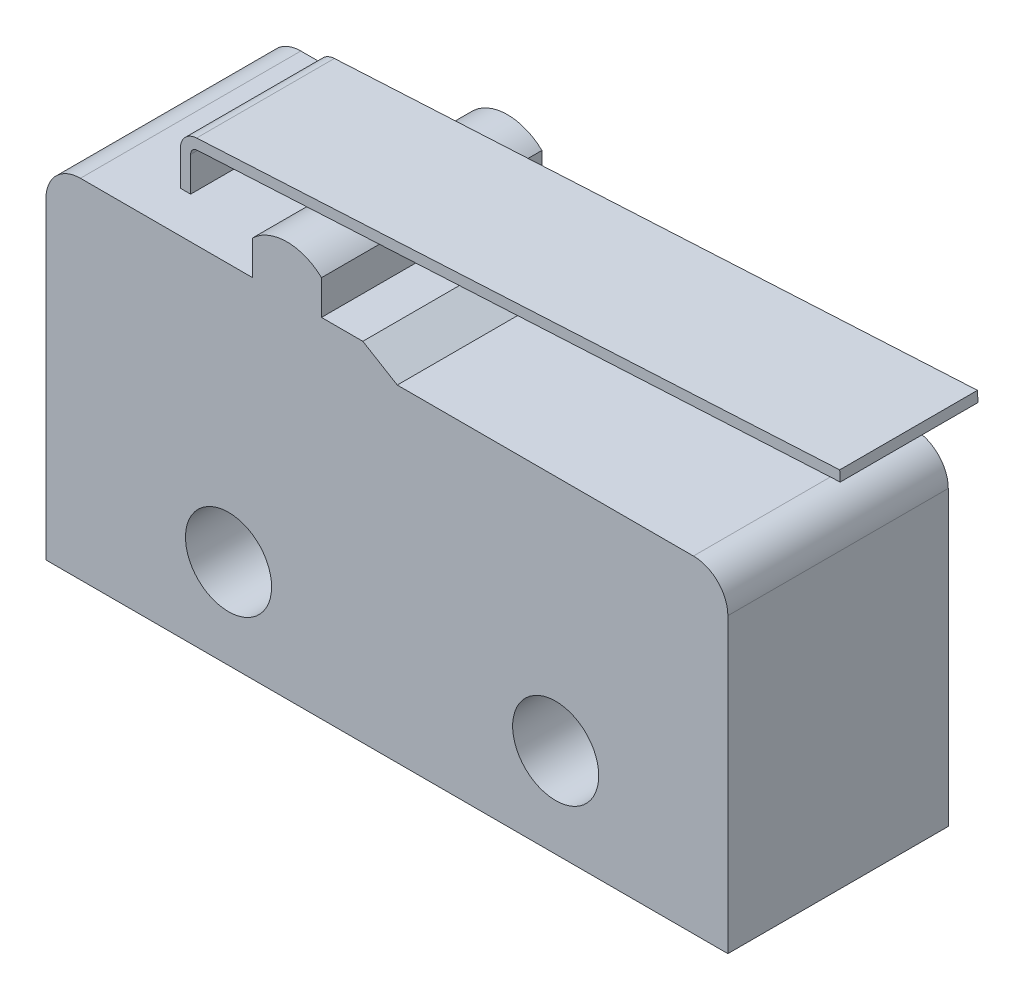
SolidWorks part; units mm, degrees
material "Nylon 6/10"
ref_plane "Front" through (0, 0, 0) normal (0, 0, 1) x (1, 0, 0)
ref_plane "Top" through (0, 0, 0) normal (0, 1, 0) x (1, 0, 0)
ref_plane "Right" through (0, 0, 0) normal (1, 0, 0) x (0, 0, -1)
sketch "Sketch1" plane through (0, 0, 0) normal (0, 0, 1) x (1, 0, 0)
  line L0 (-5.3, -2.6) -> (14.5, -2.6)
  line L1 (14.5, -2.6) -> (14.5, 5.9)
  line L2 (13.5, 6.9) -> (4.9, 6.9)
  line L3 (4.9, 6.9) -> (3.9, 7.5)
  line L4 (3.9, 7.5) -> (2.7, 7.5)
  line L5 (2.7, 7.5) -> (2.7, 8.5)
  line L6 (0.7, 8.5) -> (0.7, 7.5)
  line L7 (0.7, 7.5) -> (-4.3, 7.5)
  line L8 (-5.3, 6.5) -> (-5.3, -2.6)
  circle A0 centre (0, 0) radius 1.25
  circle A1 centre (9.5, 0) radius 1.25
  arc A2 (14.5, 5.9) -> (13.5, 6.9) centre (13.5, 5.9) ccw
  arc A3 (2.7, 8.5) -> (0.7, 8.5) centre (1.7, 7.45) ccw
  arc A4 (-4.3, 7.5) -> (-5.3, 6.5) centre (-4.3, 6.5) ccw
  dimension "D1" = 2.5
  dimension "D10" = 1
  dimension "D2" = 9.5
  dimension "D3" = 19.8
  dimension "D4" = 9.5
  dimension "D5" = 2.6
  dimension "D6" = 5.3
  dimension "D7" = 10.1
  dimension "D8" = 6
  dimension "D9" = 2
  dimension "D11" = 1.2
  dimension "D12" = 1
  dimension "D13" = 1.4
  dimension "D14" = 1
extrude "Boss-Extrude1" add sketch "Sketch1" along normal mid plane 6.4
sketch "Sketch2" plane through (0, 0, 0) normal (0, 0, 1) x (1, 0, 0)
  line L0 (-2.3, 7.5) -> (-2.3, 8.5)
  line L1 (0.7, 7.5) -> (-4.3, 7.5) construction
  line L2 (-2.1106, 8.6997) -> (16.5631, 9.6912)
  line L3 (-5.3, 6.5) -> (-5.3, -2.6) construction
  arc A0 (-2.3, 8.5) -> (-2.1106, 8.6997) centre (-2.1, 8.5) cw
  arc A1 (2.7, 8.5) -> (0.7, 8.5) centre (1.7, 7.45) ccw construction
  dimension "D4" = 0.2
  dimension "D1" = 3
  dimension "D2" = 1
  dimension "D3" = 18.7
extrude "Extrude-Thin2" add sketch "Sketch2" along normal mid plane 4 separate body thin thin type one direction reverse wall 0.3
